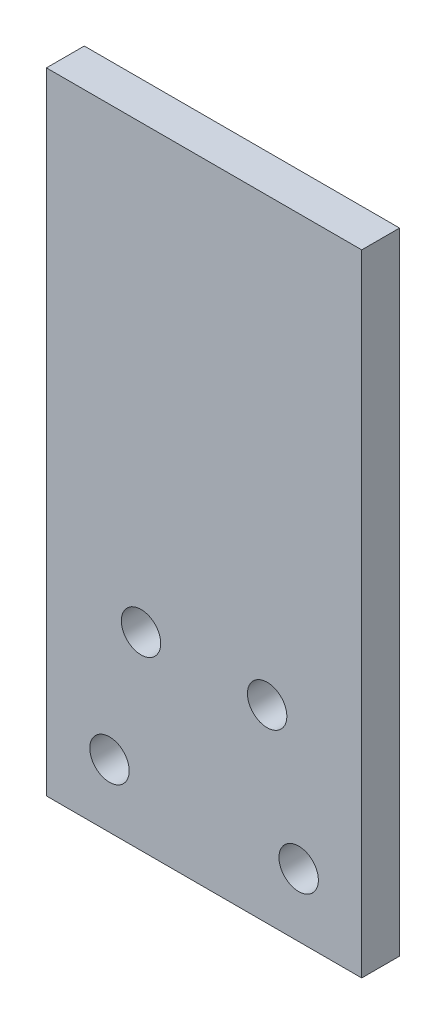
SolidWorks part; units mm, degrees
material "6061-T6 (SS)"
ref_plane "Front Plane" through (0, 0, 0) normal (0, 0, 1) x (1, 0, 0)
ref_plane "Top Plane" through (0, 0, 0) normal (0, 1, 0) x (1, 0, 0)
ref_plane "Right Plane" through (0, 0, 0) normal (1, 0, 0) x (0, 0, -1)
sketch "Sketch2" plane through (0, 0, 0) normal (0, 0, 1) x (1, 0, 0)
  line L1 (-31.75, -63.5) -> (31.75, -63.5)
  line L2 (-31.75, -63.5) -> (-31.75, 63.5)
  line L3 (-31.75, 63.5) -> (31.75, 63.5)
  line L4 (31.75, -63.5) -> (31.75, 63.5)
  line L5 (-31.75, -63.5) -> (31.75, 63.5) construction
  line L6 (-31.75, 63.5) -> (31.75, -63.5) construction
  point P0 (0, 0)
  dimension "D1" = 127
  dimension "D2" = 63.5
extrude "Boss-Extrude1" add sketch "Sketch2" along normal mid plane 7.62 contours L2 L3 L4 L1
hole_wizard "Tap Drill for 3/8-16 Tap1" positions "Sketch3" profile "Sketch4" hole size "3/8-16" standard "ANSI Inch" end condition through all
sketch "Sketch3" plane through (0, 0, 3.81) normal (0, 0, 1) x (1, 0, 0)
  line L1 (-12.7, -25.4) -> (12.7, -25.4) construction
  line L3 (-19.05, -50.8) -> (19.05, -50.8) construction
  line L5 (-31.75, -63.5) -> (31.75, -63.5) construction
  point P23 (-12.7, -25.4)
  point P24 (12.7, -25.4)
  point P27 (-19.05, -50.8)
  point P28 (19.05, -50.8)
  point P32 (0, -63.5)
  point P33 (0, -50.8)
  point P34 (0, -25.4)
  dimension "D1" = 25.4
  dimension "D2" = 38.1
  dimension "D3" = 38.1
  dimension "D4" = 12.7
sketch "Sketch4" plane through (-12.7, -25.4, 3.81) normal (1, 0, 0) x (0, -1, 0)
  line L0 (0, 0) -> (0, 7.62)
  line L1 (0, 7.62) -> (3.9687, 7.62)
  line L2 (3.9687, 7.62) -> (3.9687, 0)
  line L5 (3.9687, 0) -> (0, 0)
  line L11 (0, -6.35) -> (0, 107.95) construction
  dimension "Thru Hole Dia." = 7.9375
  dimension "Thru Hole Depth" = 7.62
